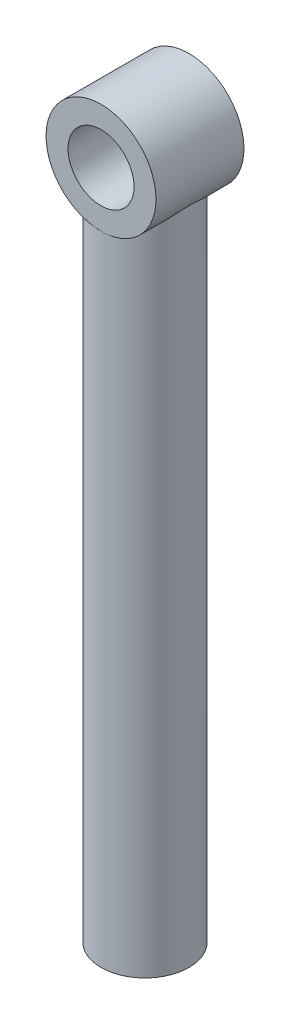
SolidWorks part; units mm, degrees
ref_plane "정면" through (0, 0, 0) normal (0, 0, 1) x (1, 0, 0)
ref_plane "윗면" through (0, 0, 0) normal (0, 1, 0) x (1, 0, 0)
ref_plane "우측면" through (0, 0, 0) normal (1, 0, 0) x (0, 0, -1)
sketch "스케치1" plane through (0, 0, 0) normal (0, 1, 0) x (1, 0, 0)
  circle A0 centre (0, 0) radius 10
  circle A1 centre (0, 0) radius 5
  dimension "D1" = 20
  dimension "D2" = 10
extrude "보스-돌출1" add sketch "스케치1" along normal mid plane 150
sketch "스케치2" plane through (0, 0, 0) normal (0, 0, 1) x (1, 0, 0)
  line L0 (0, 82.5) -> (0, 75) construction
  line L1 (10, 75) -> (-10, 75) construction
  circle A0 centre (0, 82.5) radius 12.5
  circle A1 centre (0, 82.5) radius 7.5
  dimension "D1" = 25
  dimension "D2" = 15
extrude "보스-돌출2" add sketch "스케치2" along normal mid plane 20
